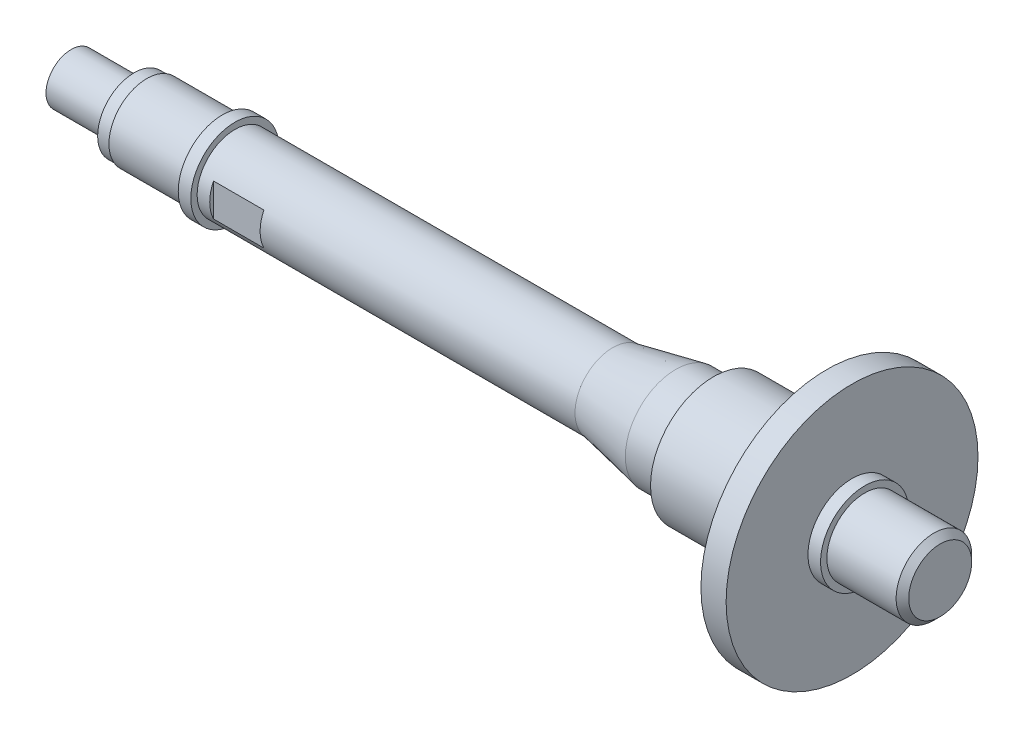
SolidWorks part; units mm, degrees
ref_plane "前视基准面" through (0, 0, 0) normal (0, 0, 1) x (1, 0, 0)
ref_plane "上视基准面" through (0, 0, 0) normal (0, 1, 0) x (1, 0, 0)
ref_plane "右视基准面" through (0, 0, 0) normal (1, 0, 0) x (0, 0, -1)
sketch "草图1" plane through (0, 0, 0) normal (1, 0, 0) x (0, 0, -1)
  circle A0 centre (0, 0) radius 10
  dimension "D1" = 20
extrude "凸台-拉伸1" add sketch "草图1" along normal blind 2
sketch "草图2" plane through (2, 0, 0) normal (1, 0, 0) x (0, 0, -1)
  circle A0 centre (0, 0) radius 3.5
  dimension "D1" = 7
extrude "凸台-拉伸2" add sketch "草图2" along normal blind 1
sketch "草图3" plane through (0, 0, 0) normal (-1, 0, 0) x (0, 0, 1)
  circle A0 centre (0, 0) radius 6
  dimension "D1" = 12
extrude "凸台-拉伸3" add sketch "草图3" along normal blind 9
sketch "草图4" plane through (-9, 0, 0) normal (-1, 0, 0) x (0, 0, 1)
  circle A0 centre (0, 0) radius 4
  dimension "D1" = 8
extrude "凸台-拉伸4" add sketch "草图4" along normal blind 3
sketch "草图5" plane through (3, 0, 0) normal (1, 0, 0) x (0, 0, -1)
  circle A0 centre (0, 0) radius 3
  dimension "D1" = 6
extrude "凸台-拉伸5" add sketch "草图5" along normal blind 6
sketch "草图6" plane through (-12, 0, 0) normal (-1, 0, 0) x (0, 0, 1)
  circle A0 centre (0, 0) radius 3
  dimension "D1" = 6
extrude "凸台-拉伸6" add sketch "草图6" along normal blind 35
sketch "草图7" plane through (-47, 0, 0) normal (-1, 0, 0) x (0, 0, 1)
  circle A0 centre (0, 0) radius 3.5
  dimension "D1" = 7
extrude "凸台-拉伸7" add sketch "草图7" along normal blind 1
sketch "草图8" plane through (-48, 0, 0) normal (-1, 0, 0) x (0, 0, 1)
  circle A0 centre (0, 0) radius 3
  dimension "D1" = 6
extrude "凸台-拉伸8" add sketch "草图8" along normal blind 9
sketch "草图9" plane through (-57, 0, 0) normal (-1, 0, 0) x (0, 0, 1)
  circle A0 centre (0, 0) radius 2
  dimension "D1" = 4
extrude "凸台-拉伸9" add sketch "草图9" along normal blind 3
chamfer "倒角1" distance 0.5 angle 45 1 edges at (9, 0, -3)
sketch "草图11" plane through (0, 0, 0) normal (0, 1, 0) x (1, 0, 0)
  line L0 (-47, 0) -> (-39.7359, 0) construction
  line L1 (-46, 3) -> (-42, 3)
  line L2 (-46, 3) -> (-46, 2.7)
  line L3 (-46, 2.7) -> (-42, 2.7)
  line L4 (-42, 3) -> (-42, 2.7)
  line L5 (-47, -3.5) -> (-47, 3.5) construction
  line L6 (-46, -3) -> (-46, -2.7)
  line L7 (-46, -2.7) -> (-42, -2.7)
  line L8 (-42, -3) -> (-42, -2.7)
  line L9 (-46, -3) -> (-42, -3)
  line L10 (-12, 3) -> (-47, 3) construction
  dimension "D1" = 4
  dimension "D2" = 0.3
  dimension "D3" = 1
  dimension "D4" = 0
extrude "切除-拉伸2" cut sketch "草图11" against normal mid plane 10
sketch "草图12" plane through (0, 0, 0) normal (-1, 0, 0) x (0, 0, 1)
  circle A0 centre (0, 0) radius 4.5
  circle A1 centre (0, 0) radius 6
  dimension "D1" = 12
  dimension "D2" = 9
extrude "切除-拉伸3" cut sketch "草图12" along normal blind 1 from offset 2
sketch "草图13" plane through (-9, 0, 0) normal (-1, 0, 0) x (0, 0, 1)
  circle A0 centre (0, 0) radius 5
  circle A1 centre (0, 0) radius 6
  dimension "D1" = 12
  dimension "D2" = 10
extrude "切除-拉伸4" cut sketch "草图13" against normal blind 6
cosmetic thread "装饰螺纹线4" parameters "D2"=9
sketch "草图14" plane through (0, 0, 0) normal (0, 0, 1) x (1, 0, 0)
  line L0 (-12, 4) -> (-17, 3)
  line L1 (-12, 3) -> (-47, 3) construction
  line L2 (-17, 3) -> (-12, 3)
  line L3 (-12, 3) -> (-12, 4)
  line L4 (-6.2386, 0) -> (-21.5744, 0) construction
  dimension "D1" = 5
revolve "旋转1" add sketch "草图14" angle 360 about L4
sketch "草图15" plane through (-57, 0, 0) normal (-1, 0, 0) x (0, 0, 1)
  circle A0 centre (0, 0) radius 2.9
  circle A1 centre (0, 0) radius 3
  dimension "D1" = 6
  dimension "D2" = 5.8
extrude "切除-拉伸5" cut sketch "草图15" against normal blind 3
sketch "草图16" plane through (-57, 0, 0) normal (-1, 0, 0) x (0, 0, 1)
  circle A0 centre (0, 0) radius 2.9
  circle A1 centre (0, 0) radius 2
extrude "切除-拉伸8" cut sketch "草图16" against normal blind 2
